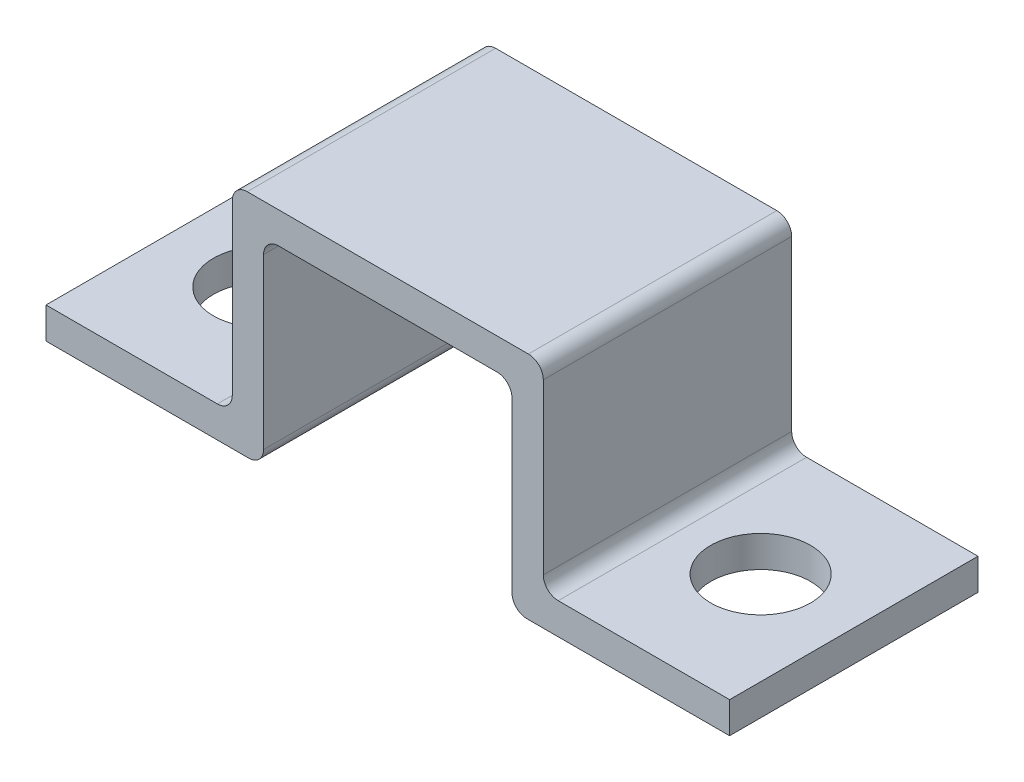
SolidWorks part; units mm, degrees
ref_plane "Front Plane" through (0, 0, 0) normal (0, 0, 1) x (1, 0, 0)
ref_plane "Top Plane" through (0, 0, 0) normal (0, 1, 0) x (1, 0, 0)
ref_plane "Right Plane" through (0, 0, 0) normal (1, 0, 0) x (0, 0, -1)
sketch "Sketch1" plane through (0, 0, 0) normal (0, 1, 0) x (1, 0, 0)
  line L1 (-6.35, -6.35) -> (6.35, -6.35)
  line L2 (-6.35, -6.35) -> (-6.35, 6.35)
  line L3 (-6.35, 6.35) -> (6.35, 6.35)
  line L4 (6.35, -6.35) -> (6.35, 6.35)
  line L5 (-6.35, -6.35) -> (6.35, 6.35) construction
  line L6 (-6.35, 6.35) -> (6.35, -6.35) construction
  point P0 (0, 0)
  dimension "D1" = 12.7
  dimension "D2" = 12.7
extrude "Boss-Extrude1" add sketch "Sketch1" along normal blind 1.6002
ref_plane "Plane1" through (6.35, 0, 0) normal (1, 0, 0) x (0, 0, -1)
sketch "Sketch2" plane through (6.35, 0, 0) normal (1, 0, 0) x (0, 0, -1)
  line L0 (6.35, 1.6002) -> (6.35, 0) construction
  line L1 (-6.35, 1.6002) -> (6.35, 1.6002)
  line L2 (-6.35, 1.6002) -> (-6.35, -10.16)
  line L3 (-6.35, -10.16) -> (6.35, -10.16)
  line L4 (6.35, 1.6002) -> (6.35, -10.16)
  line L5 (-6.35, 0) -> (6.35, 0) construction
  line L6 (-6.35, 0) -> (6.35, 0) construction
  dimension "D1" = 10.16
extrude "Boss-Extrude2" add sketch "Sketch2" along normal blind 1.6002
sketch "Sketch3" plane through (7.9502, 0, 0) normal (1, 0, 0) x (0, 0, -1)
  line L0 (6.35, -10.16) -> (6.35, 1.6002) construction
  line L1 (-6.35, -10.16) -> (6.35, -10.16)
  line L2 (-6.35, -10.16) -> (-6.35, -8.5598)
  line L3 (-6.35, -8.5598) -> (6.35, -8.5598)
  line L4 (6.35, -10.16) -> (6.35, -8.5598)
  dimension "D1" = 1.6002
extrude "Boss-Extrude3" add sketch "Sketch3" along normal blind 9.525
sketch "Sketch4" plane through (0, -8.5598, 0) normal (0, 1, 0) x (1, 0, 0)
  line L0 (12.7127, 6.35) -> (12.7127, -6.35) construction
  line L1 (17.4752, 6.35) -> (7.9502, 6.35) construction
  line L2 (17.4752, -6.35) -> (7.9502, -6.35) construction
  circle A0 centre (12.7127, 0) radius 2.5527
  dimension "D1" = 5.1054
extrude "Cut-Extrude1" cut sketch "Sketch4" against normal through all
mirror "Mirror2" about plane through (0, 0, 0) normal (1, 0, 0) of "Cut-Extrude1", "Boss-Extrude3", "Boss-Extrude2"
fillet "Fillet1" radius 0.762 8 edges at (6.35, -10.16, 0) (-6.35, -10.16, 0) (-7.9502, 1.6002, 0) (7.9502, 1.6002, 0)
